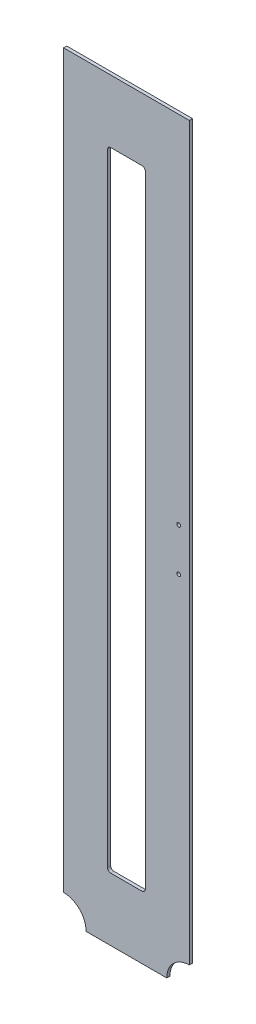
SolidWorks part; units mm, degrees
material "Acrylic (Medium-high impact)"
ref_plane "Front Plane" through (0, 0, 0) normal (0, 0, 1) x (1, 0, 0)
ref_plane "Top Plane" through (0, 0, 0) normal (0, 1, 0) x (1, 0, 0)
ref_plane "Right Plane" through (0, 0, 0) normal (1, 0, 0) x (0, 0, -1)
sketch "Sketch1" plane through (0, 0, 0) normal (0, 0, 1) x (1, 0, 0)
  line L1 (-100, -600) -> (100, -600)
  line L2 (-100, -600) -> (-100, 600)
  line L3 (-100, 600) -> (100, 600)
  line L4 (100, -600) -> (100, 600)
  line L5 (-100, -600) -> (100, 600) construction
  line L6 (-100, 600) -> (100, -600) construction
  point P0 (0, 0)
  dimension "D1" = 1200
  dimension "D2" = 200
extrude "Boss-Extrude1" add sketch "Sketch1" along normal blind 5
sketch "Sketch3" plane through (0, 0, 5) normal (0, 0, 1) x (1, 0, 0)
  line L0 (102.2135, -564.1972) -> (100, -564.1972) construction
  line L1 (-100, -600) -> (-100, -564.1972)
  line L2 (100, -600) -> (100, 600) construction
  line L3 (-64.1972, -600) -> (-100, -600)
  line L4 (-100, -600) -> (100, -600) construction
  line L6 (64.1972, -600) -> (100, -600)
  line L7 (100, -600) -> (100, -564.1972)
  line L8 (0, -600) -> (0, 597.3101) construction
  line L9 (-250, 597.3101) -> (250, 597.3101) construction
  arc A0 (100, -564.1972) -> (64.1972, -600) centre (100, -600) ccw
  arc A1 (-100, -564.1972) -> (-64.1972, -600) centre (-100, -600) cw
extrude "Cut-Extrude1" cut sketch "Sketch3" against normal through all
sketch "Sketch5" plane through (0, 0, 5) normal (0, 0, 1) x (1, 0, 0)
  line L1 (-30, -500) -> (30, -500)
  line L2 (-30, -500) -> (-30, 500)
  line L3 (-30, 500) -> (30, 500)
  line L4 (30, -500) -> (30, 500)
  line L5 (-30, -500) -> (30, 500) construction
  line L6 (-30, 500) -> (30, -500) construction
  point P0 (0, 0)
  dimension "D1" = 60
  dimension "D2" = 1000
extrude "Cut-Extrude3" cut sketch "Sketch5" against normal through all
fillet "Fillet2" radius 5 4 edges at (-30, -500, 2.5) (30, -500, 2.5) (30, 500, 2.5) (-30, 500, 2.5)
sketch "Sketch6" plane through (0, 0, 5) normal (0, 0, 1) x (1, 0, 0)
  circle A0 centre (83.1932, -34) radius 3
  circle A1 centre (83.1932, 34) radius 3
  point P4 (0, 0)
  dimension "D1" = 6
extrude "Cut-Extrude4" cut sketch "Sketch6" against normal through all
